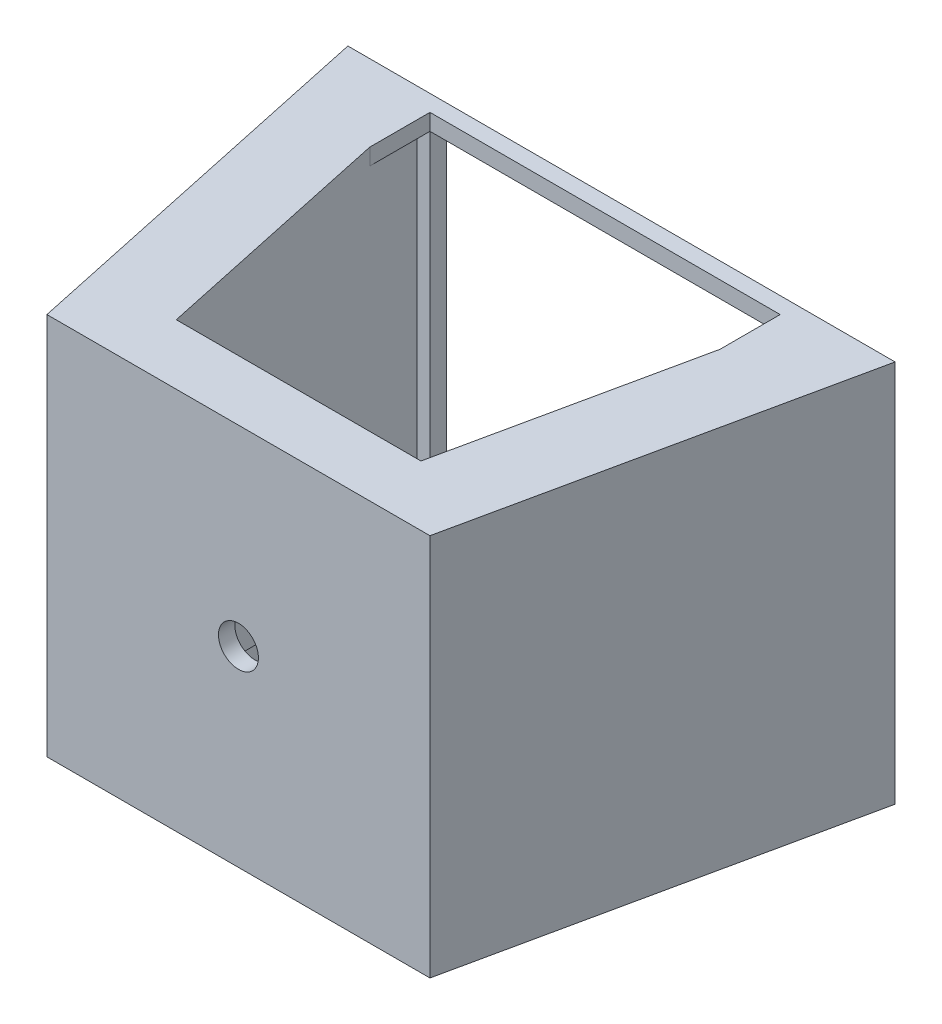
SolidWorks part; units mm, degrees
ref_plane "Piano frontale" through (0, 0, 0) normal (0, 0, 1) x (1, 0, 0)
ref_plane "Piano superiore" through (0, 0, 0) normal (0, 1, 0) x (1, 0, 0)
ref_plane "Piano destro" through (0, 0, 0) normal (1, 0, 0) x (0, 0, -1)
sketch "Schizzo1" plane through (0, 0, 0) normal (0, 0, 1) x (1, 0, 0)
  line L1 (-35, 35) -> (35, 35)
  line L2 (-35, 35) -> (-35, -35)
  line L3 (-35, -35) -> (35, -35)
  line L4 (35, 35) -> (35, -35)
  line L5 (-35, 35) -> (35, -35) construction
  line L6 (-35, -35) -> (35, 35) construction
  point P0 (0, 0)
  dimension "D2" = 70
extrude "Estrusione-Estrusione1" add sketch "Schizzo1" along normal blind 70
sketch "Schizzo3" plane through (0, 0, 0) normal (0, 0, -1) x (-1, 0, 0)
  line L0 (-35, -35) -> (-35, 35) construction
  line L1 (-32, 32) -> (32, 32)
  line L2 (-32, 32) -> (-32, -32)
  line L3 (-32, -32) -> (32, -32)
  line L4 (32, 32) -> (32, -32)
  line L5 (-32, 32) -> (32, -32) construction
  line L6 (-32, -32) -> (32, 32) construction
  point P0 (0, 0)
  dimension "D1" = 3
extrude "Taglio-Estrusione2" cut sketch "Schizzo3" against normal offset from surface (67 mm away) 3 up to face at (0, 0, 70)
sketch "Schizzo2" plane through (0, 0, 70) normal (0, 0, 1) x (1, 0, 0)
  circle A0 centre (0, 0) radius 3.65
  dimension "D1" = 7.3
extrude "Taglio-Estrusione1" cut sketch "Schizzo2" against normal up to next
sketch "Schizzo4" plane through (0, -35, 0) normal (0, -1, 0) x (1, 0, 0)
  line L0 (-35, 70) -> (-35, 0) construction
  line L1 (-32, 67) -> (32, 67)
  line L2 (-32, 67) -> (-32, 3)
  line L3 (-32, 3) -> (32, 3)
  line L4 (32, 67) -> (32, 3)
  line L5 (-32, 67) -> (32, 3) construction
  line L6 (-32, 3) -> (32, 67) construction
  line L7 (-35, 70) -> (35, 70) construction
  point P0 (0, 35)
  dimension "D1" = 3
  dimension "D2" = 3
extrude "Taglio-Estrusione3" cut sketch "Schizzo4" against normal up to next
ref_plane "Piano1" through (0, 0, 0) normal (-0.7071, 0.7071, 0) x (0, 0, 1)
mirror "Specchia1" about plane through (0, 0, 0) normal (-0.7071, 0.7071, 0) of "Taglio-Estrusione3"
mirror "Specchia2" about plane through (0, 0, 0) normal (-0.7071, 0.7071, 0) of "Specchia1", "Taglio-Estrusione3"
sketch "Schizzo5" plane through (0, 0, 67) normal (0, 0, -1) x (-1, 0, 0)
  line L0 (0, 0) -> (0, 3.65) construction
  line L1 (-21, 23.65) -> (21, 23.65)
  line L3 (-8, 4.65) -> (8, 4.65)
  line L7 (-21, 23.65) -> (-21, -9.35)
  line L10 (-21, -9.35) -> (-8, -9.35)
  line L11 (-8, 4.65) -> (-8, -9.35)
  line L14 (21, -9.35) -> (8, -9.35)
  line L15 (8, 4.65) -> (8, -9.35)
  line L16 (21, 23.65) -> (21, -9.35)
  circle A3 centre (0, 0) radius 3.65 construction
  point P0 (0, 4.65)
  point P6 (0, 0)
  point P13 (0, 3.65)
  dimension "D3" = 1
  dimension "D1" = 13
  dimension "D2" = 42
  dimension "D4" = 14
  dimension "D5" = 33
extrude "Estrusione-Estrusione2" add sketch "Schizzo5" along normal blind 15.3
sketch "Schizzo6" plane through (0, 0, 51.7) normal (0, 0, -1) x (-1, 0, 0)
  line L0 (0, 39.2219) -> (0, -42.1384) construction
  circle A0 centre (-17.5, 7.5) radius 1.5
  circle A1 centre (17.5, 7.5) radius 1.5
  dimension "D1" = 7.5
  dimension "D3" = 3
  dimension "D2" = 17.5
extrude "Taglio-Estrusione4" cut sketch "Schizzo6" against normal blind 3
sketch "Schizzo7" plane through (0, 0, 67) normal (0, 0, -1) x (-1, 0, 0)
  line L0 (-32, -35) -> (32, -35) construction
  line L1 (35, 35) -> (21, 35)
  line L2 (35, 35) -> (35, -35)
  line L3 (35, -35) -> (21, -35)
  line L4 (21, 35) -> (21, -35)
  line L5 (21, -9.35) -> (21, 23.65) construction
  line L7 (-21, 23.65) -> (-21, -9.35) construction
  line L8 (-21, -35) -> (-35, -35)
  line L9 (-21, -35) -> (-21, 35)
  line L10 (-21, 35) -> (-35, 35)
  line L11 (-35, -35) -> (-35, 35)
  line L13 (21, 23.65) -> (-21, 23.65)
  line L14 (21, 23.65) -> (21, 35)
  line L15 (21, 35) -> (-21, 35)
  line L16 (-21, 23.65) -> (-21, 35)
  line L17 (21, -35) -> (-21, -35)
  line L18 (21, -35) -> (21, -21)
  line L19 (21, -21) -> (-21, -21)
  line L20 (-21, -35) -> (-21, -21)
  line M13 (32, -35) -> (32, -32)
  line M14 (32, -32) -> (35, -32)
  line M15 (35, -32) -> (35, 32)
  line M16 (35, 32) -> (32, 32)
  line M17 (32, 32) -> (32, 35)
  line M18 (32, 35) -> (-32, 35)
  line M19 (-32, 35) -> (-32, 32)
  line M20 (-32, 32) -> (-35, 32)
  line M21 (-35, 32) -> (-35, -32)
  line M22 (-35, -32) -> (-32, -32)
  line M23 (-32, -32) -> (-32, -35)
  line M24 (-32, -35) -> (32, -35)
  line M26 (-21, -9.35) -> (-21, 23.65)
  line M27 (-21, 23.65) -> (21, 23.65)
  line M28 (21, 23.65) -> (21, -9.35)
  dimension "D1" = 14
extrude "Estrusione-Estrusione3" add sketch "Schizzo7" along normal blind 8 contours L4 L19 L9 M24 | L4 M18 M28 M24 M13 M14 M15 M16 M17 | L9 L4 M27 M18 | L9 M24 M26 M18 M19 M20 M21 M22 M23
sketch "Schizzo8" plane through (0, 0, 0) normal (0, 0, -1) x (-1, 0, 0)
  line L0 (35, -35) -> (-35, -35) construction
  line L1 (-35, 35) -> (-50, 35)
  line L2 (-35, 35) -> (-35, -35)
  line L3 (-35, -35) -> (-50, -35)
  line L4 (-50, 35) -> (-50, -35)
  dimension "D1" = 15
sketch "Schizzo9" plane through (0, -35, 0) normal (0, -1, 0) x (1, 0, 0)
  line L0 (35, 70) -> (50, 0)
sweep "Sweep1" add profiles "Schizzo8" path "Schizzo9"
mirror "Specchia4" about plane through (0, 0, 0) normal (1, 0, 0) of "Sweep1"
